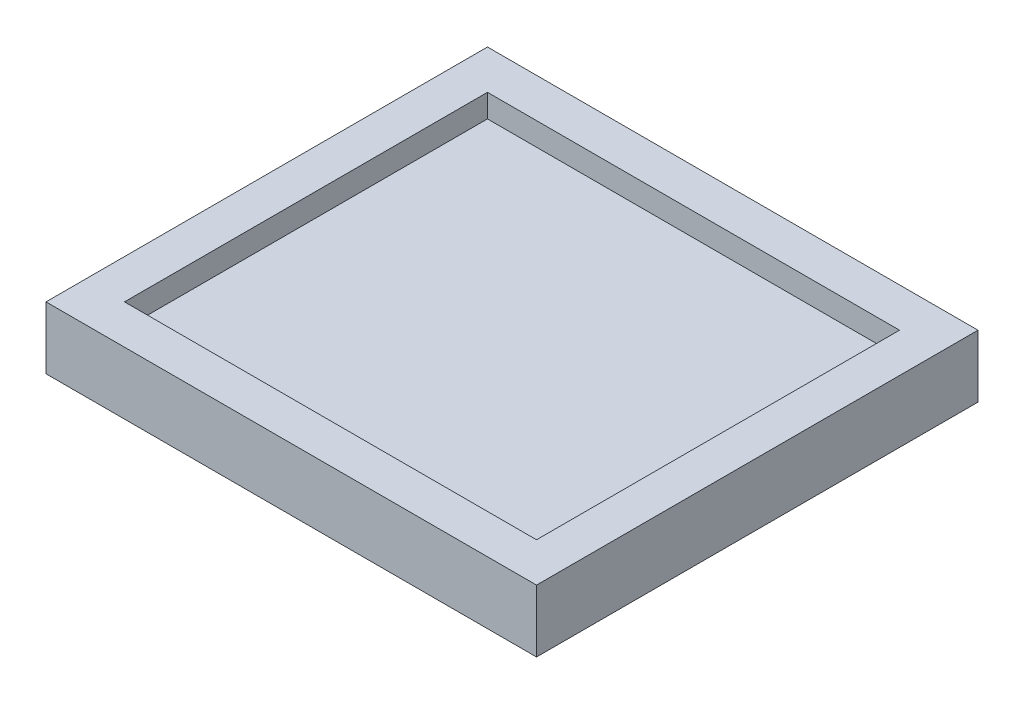
SolidWorks part; units mm, degrees
ref_plane "Front Plane" through (0, 0, 0) normal (0, 0, 1) x (1, 0, 0)
ref_plane "Top Plane" through (0, 0, 0) normal (0, 1, 0) x (1, 0, 0)
ref_plane "Right Plane" through (0, 0, 0) normal (1, 0, 0) x (0, 0, -1)
sketch "Sketch1" plane through (0, 0, 0) normal (0, 1, 0) x (1, 0, 0)
  line L1 (-50, -45) -> (50, -45)
  line L2 (-50, -45) -> (-50, 45)
  line L3 (-50, 45) -> (50, 45)
  line L4 (50, -45) -> (50, 45)
  line L5 (-50, -45) -> (50, 45) construction
  line L6 (-50, 45) -> (50, -45) construction
  point P0 (0, 0)
  dimension "D1" = 100
  dimension "D2" = 90
extrude "Boss-Extrude1" add sketch "Sketch1" along normal blind 12.7
shell "Shell1" thickness 8
